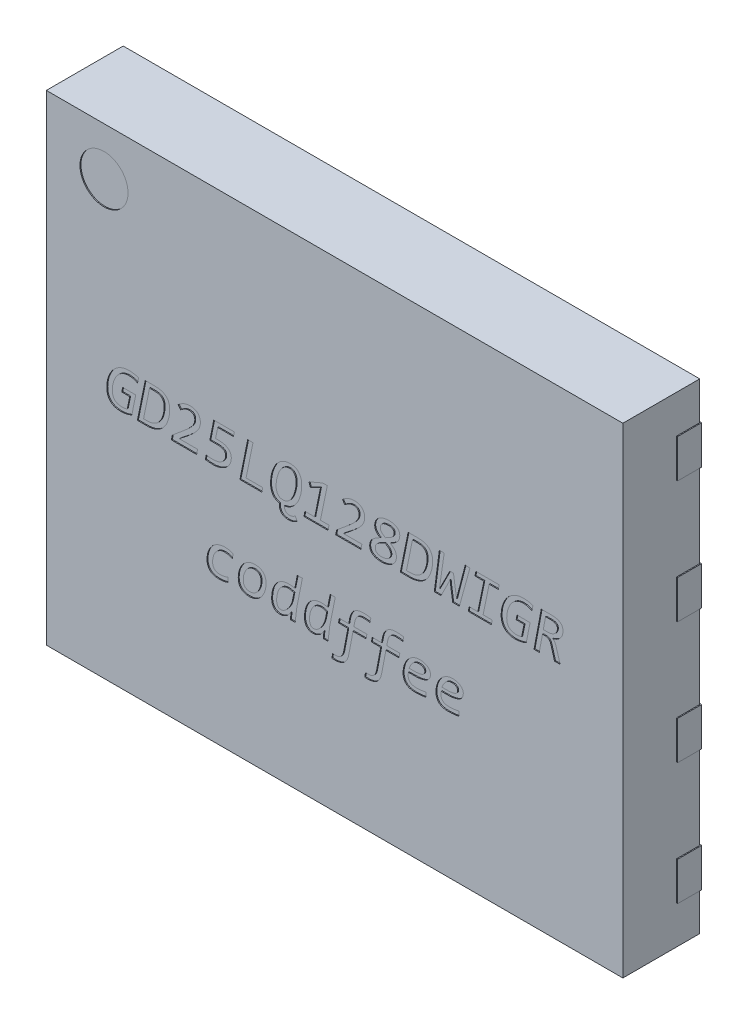
SolidWorks part; units mm, degrees
material "1023 碳钢板 (SS)"
ref_plane "前视基准面" through (0, 0, 0) normal (0, 0, 1) x (1, 0, 0)
ref_plane "上视基准面" through (0, 0, 0) normal (0, 1, 0) x (1, 0, 0)
ref_plane "右视基准面" through (0, 0, 0) normal (1, 0, 0) x (0, 0, -1)
ref_plane "芯片基底面" through (0, 0, 0.01) normal (0, 0, 1) x (1, 0, 0)
sketch "草图1" plane through (0, 0, 0.01) normal (0, 0, 1) x (1, 0, 0)
  line L1 (-3, 2.5) -> (3, 2.5)
  line L2 (-3, 2.5) -> (-3, -2.5)
  line L3 (-3, -2.5) -> (3, -2.5)
  line L4 (3, 2.5) -> (3, -2.5)
  line L5 (-3, 2.5) -> (3, -2.5) construction
  line L6 (-3, -2.5) -> (3, 2.5) construction
  point P0 (0, 0)
extrude "凸台-拉伸1" add sketch "草图1" along normal blind 0.8
sketch "草图2" plane through (0, 0, 0) normal (0, 0, 1) x (1, 0, 0)
  line L0 (-3.01, 0.435) -> (-3.01, 0.835)
  line L2 (-2.4, 0.835) -> (-3.01, 0.835)
  line L3 (-3.01, 1.705) -> (-3.01, 2.105)
  line L4 (-2.4, 2.105) -> (-3.01, 2.105)
  line L5 (-2.4, 2.105) -> (-2.4, 1.705)
  line L6 (-2.4, 1.705) -> (-3.01, 1.705)
  line L8 (-2.4, 0.835) -> (-2.4, 0.435)
  line L9 (-2.4, 0.435) -> (-3.01, 0.435)
  line L10 (-3.01, -0.835) -> (-3.01, -0.435)
  line L11 (-2.4, -0.435) -> (-3.01, -0.435)
  line L12 (-2.4, -0.435) -> (-2.4, -0.835)
  line L13 (-2.4, -0.835) -> (-3.01, -0.835)
  line L14 (-3.01, -2.105) -> (-3.01, -1.705)
  line L15 (-2.4, -1.705) -> (-3.01, -1.705)
  line L16 (-2.4, -1.705) -> (-2.4, -2.105)
  line L17 (-2.4, -2.105) -> (-3.01, -2.105)
  line L21 (2.4, -2.105) -> (3.01, -2.105)
  line L22 (2.4, -1.705) -> (2.4, -2.105)
  line L23 (2.4, -1.705) -> (3.01, -1.705)
  line L24 (3.01, -2.105) -> (3.01, -1.705)
  line L25 (2.4, -0.835) -> (3.01, -0.835)
  line L26 (2.4, -0.435) -> (2.4, -0.835)
  line L27 (2.4, -0.435) -> (3.01, -0.435)
  line L28 (3.01, -0.835) -> (3.01, -0.435)
  line L29 (2.4, 0.435) -> (3.01, 0.435)
  line L30 (2.4, 0.835) -> (2.4, 0.435)
  line L31 (2.4, 1.705) -> (3.01, 1.705)
  line L32 (2.4, 2.105) -> (2.4, 1.705)
  line L33 (2.4, 2.105) -> (3.01, 2.105)
  line L34 (3.01, 1.705) -> (3.01, 2.105)
  line L35 (2.4, 0.835) -> (3.01, 0.835)
  line L36 (3.01, 0.435) -> (3.01, 0.835)
  dimension "D1" = 4
extrude "凸台-拉伸2" add sketch "草图2" along normal blind 0.25
sketch "草图3" plane through (0, 0, 0) normal (0, 0, 1) x (1, 0, 0)
  line L0 (-1.2, 2) -> (-1.7, 1.5)
  line L1 (1.7, 2) -> (-1.2, 2)
  line L2 (1.7, 2) -> (1.7, -2)
  line L3 (1.7, -2) -> (-1.7, -2)
  line L4 (-1.7, 1.5) -> (-1.7, -2)
  line L5 (1.7, 2) -> (-1.7, -2) construction
  line L6 (1.7, -2) -> (-1.7, 2) construction
  point P0 (0, 0)
extrude "凸台-拉伸3" add sketch "草图3" along normal blind 0.01
sketch "草图4" plane through (0, 0, 0.81) normal (0, 0, 1) x (1, 0, 0)
  line L0 (-3, 0) -> (3, 0) construction
  line L2 (-3, 2.5) -> (-3, -2.5) construction
  line L3 (3, -2.5) -> (3, 2.5) construction
  line L5 (-3, -1) -> (3, -1) construction
  circle A0 centre (-2.4, 2) radius 0.25
  text T0 "<i>GD25LQ128DWIGR</i>" font "Consolas" height 0.4
  text T1 "<i>coddffee</i>" font "Consolas" height 0.4
extrude "切除-拉伸1" cut sketch "草图4" against normal blind 0.01
